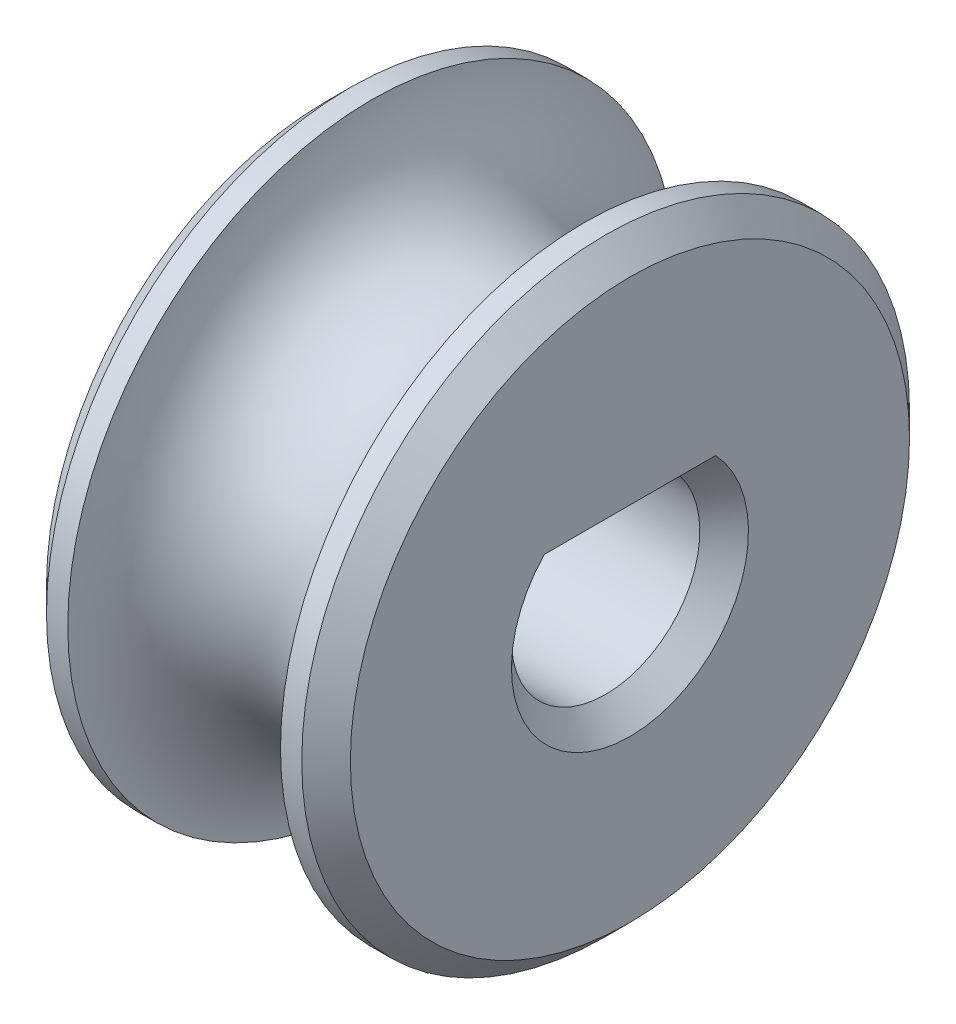
SolidWorks part; units mm, degrees
ref_plane "Front" through (0, 0, 0) normal (0, 0, 1) x (1, 0, 0)
ref_plane "Top" through (0, 0, 0) normal (0, 1, 0) x (1, 0, 0)
ref_plane "Right" through (0, 0, 0) normal (1, 0, 0) x (0, 0, -1)
sketch "Sketch1" plane through (0, 0, 0) normal (0, 0, 1) x (1, 0, 0)
  line L0 (1.75, 2.5) -> (2.5, 2.5)
  line L1 (-2.5, 2.5) -> (-1.75, 2.5)
  line L2 (-2.5, 2.5) -> (-2.5, -2.5)
  line L3 (-2.5, -2.5) -> (2.5, -2.5)
  line L4 (2.5, 2.5) -> (2.5, -2.5)
  line L5 (-2.5, 2.5) -> (2.5, -2.5) construction
  line L6 (-2.5, -2.5) -> (2.5, 2.5) construction
  arc A0 (-1.75, 2.5) -> (1.75, 2.5) centre (0, 2.5) ccw
  point P0 (0, 0)
  dimension "D3" = 3.5
  dimension "D1" = 5
  dimension "D2" = 5
revolve "Revolve1" add sketch "Sketch1" angle 360 about L3
sketch "Sketch2" plane through (2.5, 0, 0) normal (1, 0, 0) x (0, 0, -1)
  line L0 (-1.2247, -1.55) -> (1.2247, -1.55)
  arc A0 (-1.2247, -1.55) -> (1.2247, -1.55) centre (0, -2.5) ccw
  dimension "D1" = 1.55
  dimension "D2" = 2.5
extrude "Cut-Extrude1" cut sketch "Sketch2" against normal through all
chamfer "Chamfer1" distance 0.4 angle 45 6 edges at (-2.5, -1.55, 0) (-2.5, -4.05, 0) (2.5, -1.55, 0) (2.5, -4.05, 0) (2.5, -2.5, 5) (-2.5, -2.5, 5)
